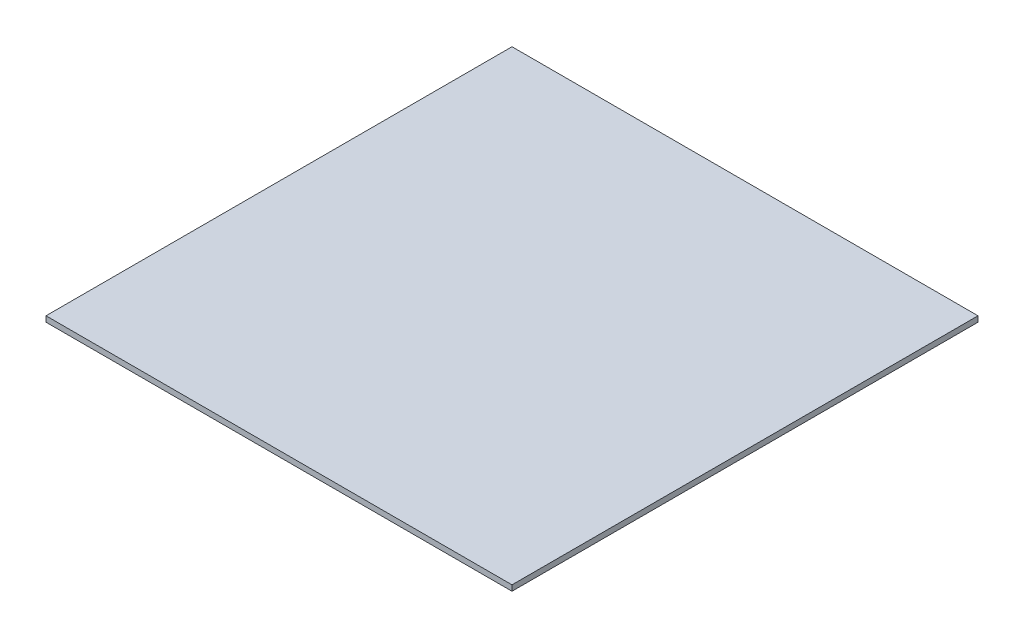
SolidWorks part; units mm, degrees
material "Pine"
ref_plane "Front Plane" through (0, 0, 0) normal (0, 0, 1) x (1, 0, 0)
ref_plane "Top Plane" through (0, 0, 0) normal (0, 1, 0) x (1, 0, 0)
ref_plane "Right Plane" through (0, 0, 0) normal (1, 0, 0) x (0, 0, -1)
sketch "Sketch1" plane through (0, 0, 0) normal (0, 1, 0) x (1, 0, 0)
  line L1 (0, 0) -> (500, 0)
  line L2 (0, 0) -> (0, 500)
  line L3 (0, 500) -> (500, 500)
  line L4 (500, 0) -> (500, 500)
  dimension "D1" = 500
  dimension "D2" = 500
extrude "Boss-Extrude1" add sketch "Sketch1" along normal blind 6
